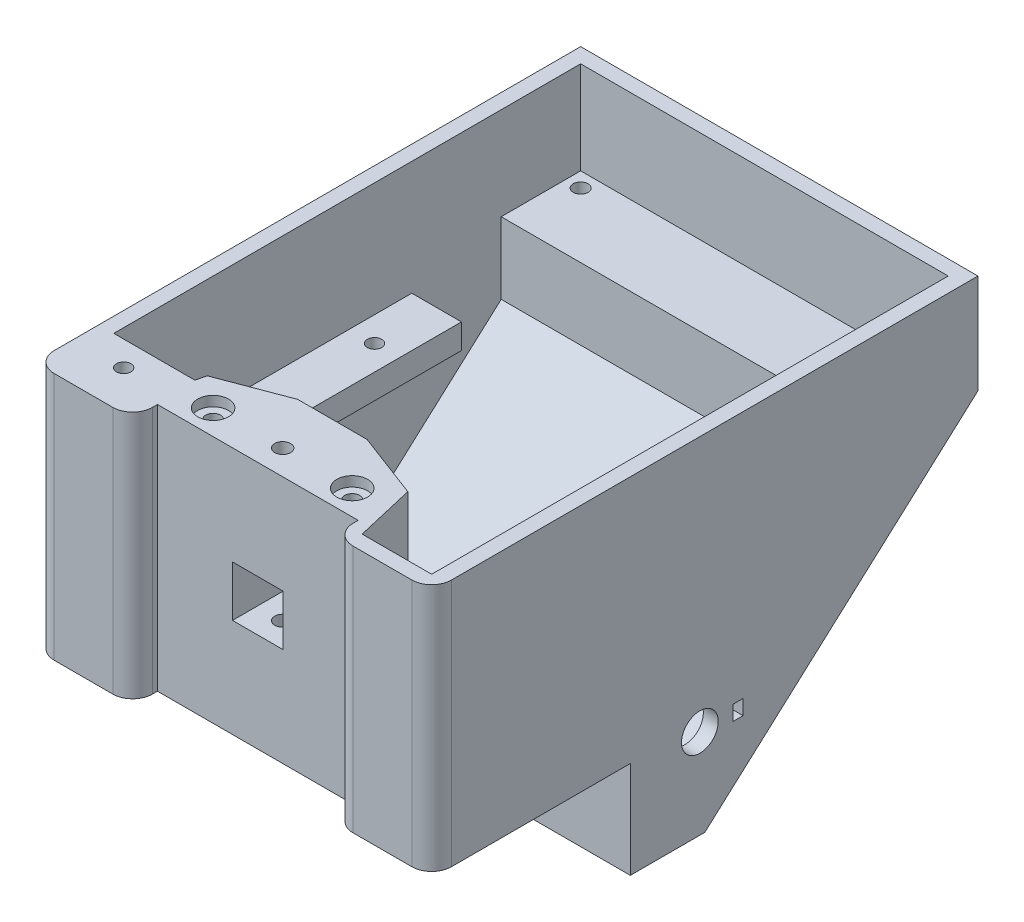
SolidWorks part; units mm, degrees
ref_plane "Спереди" through (0, 0, 0) normal (0, 0, 1) x (1, 0, 0)
ref_plane "Сверху" through (0, 0, 0) normal (0, 1, 0) x (1, 0, 0)
ref_plane "Справа" through (0, 0, 0) normal (1, 0, 0) x (0, 0, -1)
sketch "Sketch2" plane through (0, 0, 0) normal (1, 0, 0) x (0, 0, -1)
  line L0 (-27.3205, 20.9982) -> (-27.3205, -29.0018)
  line L1 (-27.3205, -29.0018) -> (12.6795, -29.0018)
  line L2 (12.6795, -29.0018) -> (12.6795, -48.5114)
  line L3 (12.6795, -48.5114) -> (27.6795, -48.5114)
  line L4 (82.6795, 20.9982) -> (82.6795, 0.9982)
  line L5 (82.6795, 20.9982) -> (-27.3205, 20.9982)
  line L6 (82.6795, 0.9982) -> (27.6795, -48.5114)
  dimension "D1" = 110
  dimension "D2" = 50
  dimension "D3" = 40
  dimension "D4" = 15
  dimension "D5" = 20
extrude "Boss-Extrude1" add sketch "Sketch2" along normal blind 80
shell "Shell1" thickness 3
sketch "Sketch3" plane through (0, 0, 24.3205) normal (0, 0, -1) x (-1, 0, 0)
  line L0 (-40, 20.9982) -> (-40, -26.0018) construction
  line L3 (-77, 20.9982) -> (-3, 20.9982) construction
  line L4 (-77, -26.0018) -> (-3, -26.0018) construction
  line L6 (-17, 20.9982) -> (-63, 20.9982)
  line L7 (-17, 20.9982) -> (-17, -26.0018)
  line L8 (-17, -26.0018) -> (-63, -26.0018)
  line L9 (-63, 20.9982) -> (-63, -26.0018)
  line L10 (-17, 20.9982) -> (-63, -26.0018) construction
  line L11 (-17, -26.0018) -> (-63, 20.9982) construction
  point P6 (-40, -2.5018)
  dimension "D1" = 46
extrude "Boss-Extrude2" add sketch "Sketch3" along normal blind 17
sketch "Sketch4" plane through (0, 0, 27.3205) normal (0, 0, 1) x (1, 0, 0)
  line L0 (0, 20.9982) -> (80, -29.0018) construction
  line L2 (45.1, -9.1018) -> (34.9, -9.1018)
  line L3 (45.1, -9.1018) -> (45.1, 1.0982)
  line L4 (45.1, 1.0982) -> (34.9, 1.0982)
  line L5 (34.9, -9.1018) -> (34.9, 1.0982)
  line L6 (45.1, -9.1018) -> (34.9, 1.0982) construction
  line L7 (45.1, 1.0982) -> (34.9, -9.1018) construction
  point P4 (40, -4.0018)
  dimension "D1" = 10.2
extrude "Cut-Extrude1" cut sketch "Sketch4" against normal up to surface (20 mm away) up to face at (40, -2.5018, 7.3205)
sketch "Sketch6" plane through (0, -29.0018, 0) normal (0, -1, 0) x (1, 0, 0)
  line L0 (40, 27.3205) -> (40, -12.6795) construction
  line L1 (47.5, -5.4795) -> (32.5, -5.4795)
  line L2 (47.5, -5.4795) -> (47.5, 7.3205)
  line L3 (47.5, 7.3205) -> (32.5, 7.3205)
  line L4 (32.5, -5.4795) -> (32.5, 7.3205)
  line L5 (47.5, -5.4795) -> (32.5, 7.3205) construction
  line L6 (47.5, 7.3205) -> (32.5, -5.4795) construction
  line L7 (80, -12.6795) -> (0, -12.6795) construction
  line L9 (80, 27.3205) -> (0, 27.3205) construction
  point P0 (40, 0.9205)
  dimension "D1" = 15
  dimension "D2" = 12.8
  dimension "D4" = 20
extrude "Cut-Extrude2" cut sketch "Sketch6" against normal up to surface (3 mm away) up to face at (40, -26.0018, 10.0705)
sketch "Sketch7" plane through (0, 0, 27.3205) normal (0, 0, 1) x (1, 0, 0)
  line L0 (40, 20.9982) -> (40, -29.0018) construction
  line L1 (80, 20.9982) -> (0, 20.9982) construction
  line L2 (80, -29.0018) -> (0, -29.0018) construction
  line L4 (60.2, -29.0018) -> (19.8, -29.0018)
  line L5 (60.2, -29.0018) -> (60.2, 20.9982)
  line L6 (60.2, 20.9982) -> (19.8, 20.9982)
  line L7 (19.8, -29.0018) -> (19.8, 20.9982)
  line L8 (60.2, -29.0018) -> (19.8, 20.9982) construction
  line L9 (60.2, 20.9982) -> (19.8, -29.0018) construction
  point P6 (40, -4.0018)
  dimension "D1" = 40.4
extrude "Cut-Extrude3" cut sketch "Sketch7" against normal blind 5
fillet "Fillet1" radius 4 4 edges at (19.8, -4.0018, 27.3205) (60.2, -4.0018, 27.3205) (80, -4.0018, 27.3205) (0, -4.0018, 27.3205)
sketch "Sketch12" plane through (0, 20.9982, 0) normal (0, 1, 0) x (1, 0, 0)
  line L0 (19.8, -22.3205) -> (19.8, -12.3205) construction
  line L1 (19.8, -12.3205) -> (60.2, -12.3205) construction
  line L2 (60.2, -12.3205) -> (60.2, -22.3205) construction
  line L3 (33, -7.3205) -> (19.8, -12.3205)
  line L4 (17, -7.3205) -> (63, -7.3205) construction
  line L5 (19.8, -12.3205) -> (17, -24.3205)
  line L6 (17, -24.3205) -> (17, -7.3205)
  line L7 (17, -7.3205) -> (33, -7.3205)
  line L8 (47, -7.3205) -> (63, -7.3205)
  line L9 (63, -7.3205) -> (63, -24.3205)
  line L10 (63, -24.3205) -> (60.2, -12.3205)
  line L11 (60.2, -12.3205) -> (47, -7.3205)
  dimension "D1" = 10
  dimension "D2" = 16
extrude "Cut-Extrude7" cut sketch "Sketch12" against normal up to surface (47 mm away) up to face at (40, -26.0018, 7.0205)
sketch "Sketch13" plane through (0, 20.9982, 0) normal (0, 1, 0) x (1, 0, 0)
  line L0 (19.8, -22.3205) -> (19.8, -12.3205) construction
  line L1 (19.8, -12.3205) -> (60.2, -12.3205) construction
  line L2 (60.2, -12.3205) -> (60.2, -22.3205) construction
  line L3 (60.2, -17.3205) -> (19.8, -17.3205) construction
  circle A0 centre (26, -17.3205) radius 1.5
  circle A1 centre (54, -17.3205) radius 1.5
  point P14 (40, -17.3205)
  dimension "D1" = 3
  dimension "D2" = 28
  dimension "D3" = 14
  dimension "D4" = 6.2
extrude "Cut-Extrude8" cut sketch "Sketch13" against normal blind 25
sketch "Sketch14" plane through (0, 20.9982, 0) normal (0, 1, 0) x (1, 0, 0)
  circle A0 centre (26, -17.3205) radius 3.1
  circle A1 centre (54, -17.3205) radius 3.1
  dimension "D1" = 6.2
extrude "Cut-Extrude9" cut sketch "Sketch14" against normal blind 2
sketch "Sketch17" plane through (77, 0, 0) normal (-1, 0, 0) x (0, 0, 1)
  line L0 (-45.6795, -2.0018) -> (-0.6795, -2.0018)
  line L1 (-0.6795, -2.0018) -> (-0.6795, -7.0018)
  line L2 (-0.6795, -7.0018) -> (-45.6795, -7.0018)
  line L3 (-45.6795, -7.0018) -> (-45.6795, -2.0018)
  line L4 (-79.6795, 20.9982) -> (24.3205, 20.9982) construction
  line L5 (-79.6795, 2.3342) -> (-79.6795, 20.9982) construction
  dimension "D1" = 45
  dimension "D2" = 5
  dimension "D3" = 23
  dimension "D4" = 34
extrude "Boss-Extrude5" add sketch "Sketch17" along normal up to surface (74 mm away) up to face at (3, -14.0994, -24.0865)
sketch "Sketch18" plane through (0, -2.0018, 0) normal (0, 1, 0) x (1, 0, 0)
  line L0 (40, 0.6795) -> (40, 45.6795) construction
  line L1 (3, 0.6795) -> (77, 0.6795) construction
  line L2 (3, 45.6795) -> (77, 45.6795) construction
  line L3 (77, 0.6795) -> (77, 45.6795) construction
  line L4 (13, 0.6795) -> (67, 0.6795)
  line L5 (13, 0.6795) -> (13, 45.6795)
  line L6 (13, 45.6795) -> (67, 45.6795)
  line L7 (67, 0.6795) -> (67, 45.6795)
  line L8 (13, 0.6795) -> (67, 45.6795) construction
  line L9 (13, 45.6795) -> (67, 0.6795) construction
  point P6 (40, 23.1795)
  dimension "D1" = 10
extrude "Cut-Extrude10" cut sketch "Sketch18" against normal up to next
sketch "Sketch19" plane through (0, -2.0018, 0) normal (0, 1, 0) x (1, 0, 0)
  line L0 (72, 45.6795) -> (72, 0.6795) construction
  line L1 (67, 45.6795) -> (77, 45.6795) construction
  line L2 (67, 0.6795) -> (77, 0.6795) construction
  line L3 (8, 45.6795) -> (8, 0.6795) construction
  line L4 (3, 45.6795) -> (13, 45.6795) construction
  line L5 (3, 0.6795) -> (13, 0.6795) construction
  circle A0 centre (72, 37.1795) radius 1.45
  circle A1 centre (72, 6.1795) radius 1.45
  circle A2 centre (8, 33.1795) radius 1.45
  circle A3 centre (8, 6.1795) radius 1.45
  point P20 (72, 23.1795)
  point P21 (8, 23.1795)
  dimension "D1" = 2.9
  dimension "D2" = 14
  dimension "D3" = 17
  dimension "D4" = 17
  dimension "D5" = 10
extrude "Cut-Extrude11" cut sketch "Sketch19" against normal up to next
sketch "Sketch21" plane through (0, -26.0018, 0) normal (0, 1, 0) x (1, 0, 0)
  line L0 (3, -24.3205) -> (3, -14.3205)
  line L1 (3, -24.3205) -> (3, 15.6795) construction
  line L2 (3, -14.3205) -> (19.3333, -14.3205)
  line L3 (19.8, -12.3205) -> (17, -24.3205) construction
  line L4 (19.3333, -14.3205) -> (17, -24.3205)
  line L6 (3, -24.3205) -> (17, -24.3205)
  dimension "D1" = 10
extrude "Boss-Extrude6" add sketch "Sketch21" along normal up to surface (47 mm away) up to face at (54, 20.9982, 20.4205)
sketch "Sketch22" plane through (0, 20.9982, 0) normal (0, 1, 0) x (1, 0, 0)
  line L0 (0, 82.6795) -> (0, -23.3205) construction
  line L1 (15.8, -27.3205) -> (4, -27.3205) construction
  circle A0 centre (10, -19.3205) radius 1.45
  dimension "D1" = 2.9
  dimension "D2" = 10
  dimension "D3" = 8
extrude "Cut-Extrude12" cut sketch "Sketch22" against normal through all
sketch "Sketch24" plane through (80, 0, 0) normal (1, 0, 0) x (0, 0, -1)
  line L0 (12.6795, -48.5114) -> (27.6795, -48.5114) construction
  line L1 (12.6795, -29.0018) -> (12.6795, -48.5114) construction
  line L2 (18.1795, -30.5114) -> (18.1795, -19.0114) construction
  line L3 (18.1795, -19.0114) -> (35.1795, -19.0114) construction
  line L4 (35.1795, -19.0114) -> (35.1795, -30.5114) construction
  line L5 (26.6795, -19.0114) -> (26.6795, -39.0114) construction
  line L6 (30.3795, -30.5114) -> (34.3795, -30.5114) construction
  line L8 (33.3795, -32.0114) -> (35.3795, -32.0114)
  line L9 (33.3795, -32.0114) -> (33.3795, -29.0114)
  line L10 (33.3795, -29.0114) -> (35.3795, -29.0114)
  line L11 (35.3795, -32.0114) -> (35.3795, -29.0114)
  line L12 (33.3795, -32.0114) -> (35.3795, -29.0114) construction
  line L13 (33.3795, -29.0114) -> (35.3795, -32.0114) construction
  circle A0 centre (26.6795, -30.5114) radius 3.7
  circle A1 centre (26.6795, -30.5114) radius 8.5 construction
  dimension "D1" = 7.4
  dimension "D2" = 17
  dimension "D3" = 18
  dimension "D4" = 14
  dimension "D5" = 20
  dimension "D6" = 4
  dimension "D7" = 2
  dimension "D8" = 3
extrude "Cut-Extrude13" cut sketch "Sketch24" against normal up to next
sketch "Sketch26" plane through (3, 0, 0) normal (1, 0, 0) x (0, 0, -1)
  line L0 (79.6795, 2.3342) -> (63.6795, 2.3342)
  line L1 (63.6795, 2.3342) -> (63.6795, -12.0686)
  line L2 (26.5281, -45.5114) -> (79.6795, 2.3342) construction
  line L3 (63.6795, -12.0686) -> (79.6795, 2.3342)
  dimension "D1" = 16
extrude "Boss-Extrude7" add sketch "Sketch26" along normal up to surface (74 mm away) up to face at (77, -30.5114, -34.3795)
sketch "Sketch27" plane through (0, 2.3342, 0) normal (0, 1, 0) x (1, 0, 0)
  line L0 (3, 76.6795) -> (77, 76.6795) construction
  line L1 (3, 79.6795) -> (3, 63.6795) construction
  line L2 (77, 79.6795) -> (77, 63.6795) construction
  line L3 (80, 82.6795) -> (0, 82.6795) construction
  circle A0 centre (6, 76.6795) radius 1.5
  circle A1 centre (74, 76.6795) radius 1.5
  point P10 (40, 76.6795)
  dimension "D1" = 3
  dimension "D2" = 68
  dimension "D3" = 34
  dimension "D4" = 6
extrude "Cut-Extrude14" cut sketch "Sketch27" against normal blind 10
sketch "Sketch28" plane through (0, 2.3342, 0) normal (0, 1, 0) x (1, 0, 0)
  line L1 (74, 79.9295) -> (71.1854, 78.3045)
  line L2 (71.1854, 78.3045) -> (71.1854, 75.0545)
  line L3 (71.1854, 75.0545) -> (74, 73.4295)
  line L4 (74, 73.4295) -> (76.8146, 75.0545)
  line L5 (76.8146, 75.0545) -> (76.8146, 78.3045)
  line L6 (76.8146, 78.3045) -> (74, 79.9295)
  line L7 (6, 73.4295) -> (8.8146, 75.0545)
  line L8 (8.8146, 75.0545) -> (8.8146, 78.3045)
  line L9 (8.8146, 78.3045) -> (6, 79.9295)
  line L10 (6, 79.9295) -> (3.1854, 78.3045)
  line L11 (3.1854, 78.3045) -> (3.1854, 75.0545)
  line L12 (3.1854, 75.0545) -> (6, 73.4295)
  circle A0 centre (74, 76.6795) radius 3.25 construction
  circle A1 centre (6, 76.6795) radius 3.25 construction
  dimension "D1" = 6.5
extrude "Cut-Extrude15" cut sketch "Sketch28" against normal blind 32 from offset 3 offset against normal yes
sketch "Sketch29" plane through (0, -29.0018, 0) normal (0, -1, 0) x (1, 0, 0)
  line L0 (0, 23.3205) -> (0, -12.6795) construction
  line L1 (7.1854, 17.6955) -> (10, 16.0705)
  line L2 (10, 16.0705) -> (12.8146, 17.6955)
  line L3 (12.8146, 17.6955) -> (12.8146, 20.9455)
  line L4 (12.8146, 20.9455) -> (10, 22.5705)
  line L5 (10, 22.5705) -> (7.1854, 20.9455)
  line L6 (7.1854, 20.9455) -> (7.1854, 17.6955)
  circle A0 centre (10, 19.3205) radius 3.25 construction
  dimension "D1" = 6.5
extrude "Cut-Extrude16" cut sketch "Sketch29" against normal blind 30
sketch "Sketch30" plane through (0, -26.0018, 0) normal (0, 1, 0) x (1, 0, 0)
  line L0 (77, -24.3205) -> (63, -24.3205)
  line L1 (63, -24.3205) -> (60.2, -12.3205)
  line L2 (63, -24.3205) -> (60.2, -12.3205) construction
  line L3 (60.2, -12.3205) -> (77, -12.3205)
  line L4 (77, -24.3205) -> (77, 15.6795) construction
  line L5 (77, -12.3205) -> (77, -24.3205)
  dimension "D1" = 12
extrude "Boss-Extrude8" add sketch "Sketch30" along normal blind 20
sketch "Sketch31" plane through (0, -6.0018, 0) normal (0, 1, 0) x (1, 0, 0)
  line L0 (76, -27.3205) -> (64.2, -27.3205) construction
  line L1 (80, -23.3205) -> (80, 12.6795) construction
  circle A0 centre (72, -21.3205) radius 1.5
  dimension "D3" = 3
  dimension "D1" = 6
  dimension "D2" = 8
extrude "Cut-Extrude17" cut sketch "Sketch31" against normal through all
sketch "Sketch32" plane through (0, -29.0018, 0) normal (0, -1, 0) x (1, 0, 0)
  line L1 (72, 24.5705) -> (69.1854, 22.9455)
  line L2 (69.1854, 22.9455) -> (69.1854, 19.6955)
  line L3 (69.1854, 19.6955) -> (72, 18.0705)
  line L4 (72, 18.0705) -> (74.8146, 19.6955)
  line L5 (74.8146, 19.6955) -> (74.8146, 22.9455)
  line L6 (74.8146, 22.9455) -> (72, 24.5705)
  circle A0 centre (72, 21.3205) radius 3.25 construction
  dimension "D1" = 6.5
extrude "Cut-Extrude18" cut sketch "Sketch32" against normal blind 15
sketch "Sketch33" plane through (0, -2.0018, 0) normal (0, 1, 0) x (1, 0, 0)
  line L0 (67, 40.6795) -> (77, 40.6795)
  line L1 (67, 0.6795) -> (67, 45.6795) construction
  line L2 (77, 0.6795) -> (77, 45.6795) construction
  line L3 (77, 40.6795) -> (77, 45.6795)
  line L4 (77, 45.6795) -> (67, 45.6795)
  line L5 (67, 45.6795) -> (67, 40.6795)
  dimension "D1" = 5
extrude "Cut-Extrude19" cut sketch "Sketch33" against normal up to next
sketch "Sketch34" plane through (0, 20.9982, 0) normal (0, 1, 0) x (1, 0, 0)
  line L0 (54, -17.3205) -> (26, -17.3205) construction
  circle A0 centre (40, -17.3205) radius 1.6
  dimension "D1" = 3.2
extrude "Cut-Extrude20" cut sketch "Sketch34" against normal through all
sketch "Sketch36" plane through (0, -29.0018, 0) normal (0, -1, 0) x (1, 0, 0)
  line L1 (38.375, 20.1351) -> (36.75, 17.3205)
  line L2 (36.75, 17.3205) -> (38.375, 14.5059)
  line L3 (38.375, 14.5059) -> (41.625, 14.5059)
  line L4 (41.625, 14.5059) -> (43.25, 17.3205)
  line L5 (43.25, 17.3205) -> (41.625, 20.1351)
  line L6 (41.625, 20.1351) -> (38.375, 20.1351)
  circle A0 centre (40, 17.3205) radius 3.25 construction
  dimension "D1" = 6.5
extrude "Cut-Extrude22" cut sketch "Sketch36" against normal blind 14
